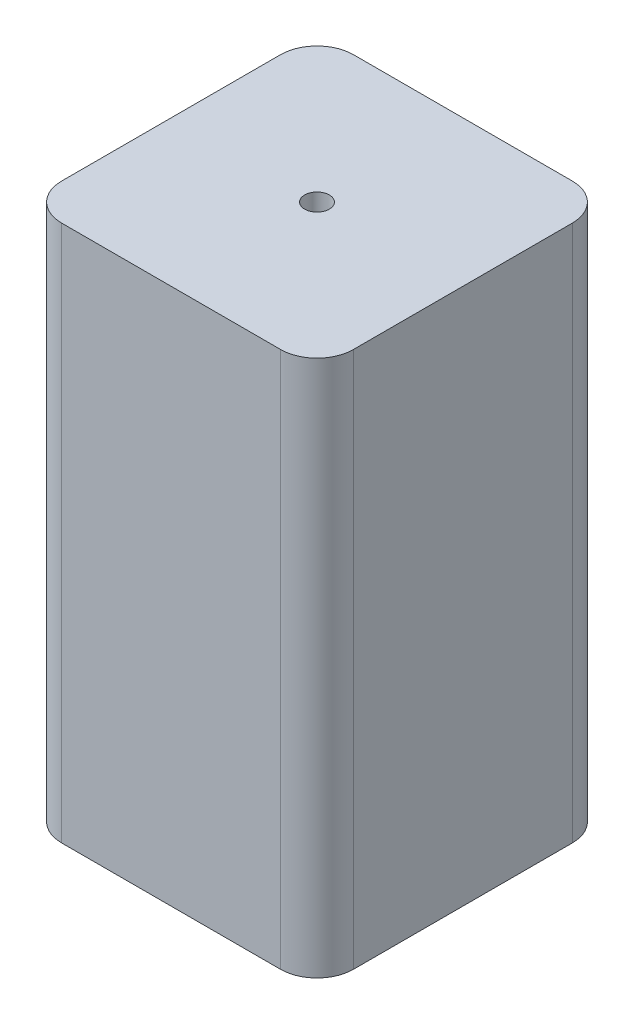
SolidWorks part; units mm, degrees
ref_plane "Front" through (0, 0, 0) normal (0, 0, 1) x (1, 0, 0)
ref_plane "Top" through (0, 0, 0) normal (0, 1, 0) x (1, 0, 0)
ref_plane "Right" through (0, 0, 0) normal (1, 0, 0) x (0, 0, -1)
sketch "Sketch1" plane through (0, 0, 0) normal (0, 1, 0) x (1, 0, 0)
  line L0 (-25, 25) -> (25, -25) construction
  line L1 (-25, 25) -> (25, 25)
  line L2 (-25, 25) -> (-25, -25)
  line L3 (-25, -25) -> (25, -25)
  line L4 (25, 25) -> (25, -25)
  dimension "D1" = 50
extrude "Boss-Extrude1" add sketch "Sketch1" along normal blind 92
sketch "Sketch2" plane through (0, 92, 0) normal (0, 1, 0) x (1, 0, 0)
  circle A0 centre (0, 0) radius 2.115
  dimension "D1" = 4.23
extrude "Cut-Extrude1" cut sketch "Sketch2" against normal blind 20
fillet "Fillet1" radius 6.25 4 edges at (-25, 46, 25) (-25, 46, -25) (25, 46, -25) (25, 46, 25)
